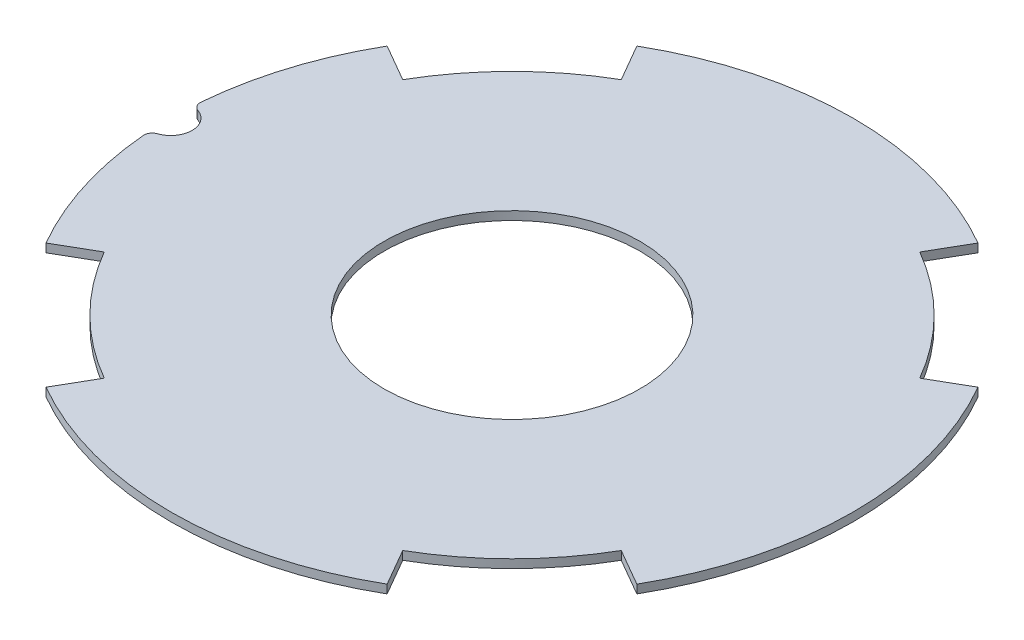
SolidWorks part; units mm, degrees
ref_plane "Front Plane" through (0, 0, 0) normal (0, 0, 1) x (1, 0, 0)
ref_plane "Top Plane" through (0, 0, 0) normal (0, 1, 0) x (1, 0, 0)
ref_plane "Right Plane" through (0, 0, 0) normal (1, 0, 0) x (0, 0, -1)
sketch "Sketch1" plane through (0, 0, 0) normal (0, 1, 0) x (1, 0, 0)
  line L2 (34.641, -20) -> (30.3109, -17.5)
  line L3 (-34.641, -20) -> (-30.3109, -17.5)
  line L4 (-20, 34.641) -> (-17.5, 30.3109)
  line L5 (-20, -34.641) -> (-17.5, -30.3109)
  line L7 (-30.3109, 17.5) -> (-34.641, 20)
  line L12 (17.5, -30.3109) -> (20, -34.641)
  line L15 (30.3109, 17.5) -> (34.641, 20)
  line L16 (17.5, 30.3109) -> (20, 34.641)
  arc A0 (-39.8558, -3.3938) -> (-34.641, -20) centre (0, 0) ccw
  circle A1 centre (0, 0) radius 15
  arc A2 (-39.1853, -2.3635) -> (-39.1853, 2.3635) centre (-40, 0) ccw
  arc A3 (-39.1853, 2.3635) -> (-39.8558, 3.3938) centre (-38.8594, 3.3089) cw
  arc A4 (-39.8558, -3.3938) -> (-39.1853, -2.3635) centre (-38.8594, -3.3089) cw
  arc A5 (-17.5, 30.3109) -> (-30.3109, 17.5) centre (0, 0) ccw
  arc A6 (-34.641, 20) -> (-39.8558, 3.3938) centre (0, 0) ccw
  arc A7 (-20, -34.641) -> (20, -34.641) centre (0, 0) ccw
  arc A8 (34.641, -20) -> (34.641, 20) centre (0, 0) ccw
  arc A9 (20, 34.641) -> (-20, 34.641) centre (0, 0) ccw
  arc A10 (-30.3109, -17.5) -> (-17.5, -30.3109) centre (0, 0) ccw
  arc A11 (30.3109, 17.5) -> (17.5, 30.3109) centre (0, 0) ccw
  arc A12 (17.5, -30.3109) -> (30.3109, -17.5) centre (0, 0) ccw
  dimension "D1" = 80
  dimension "D2" = 30
  dimension "D3" = 5
  dimension "D4" = 1
  dimension "D5" = 1
  dimension "D6" = 70
extrude "Boss-Extrude1" add sketch "Sketch1" along normal blind 1
